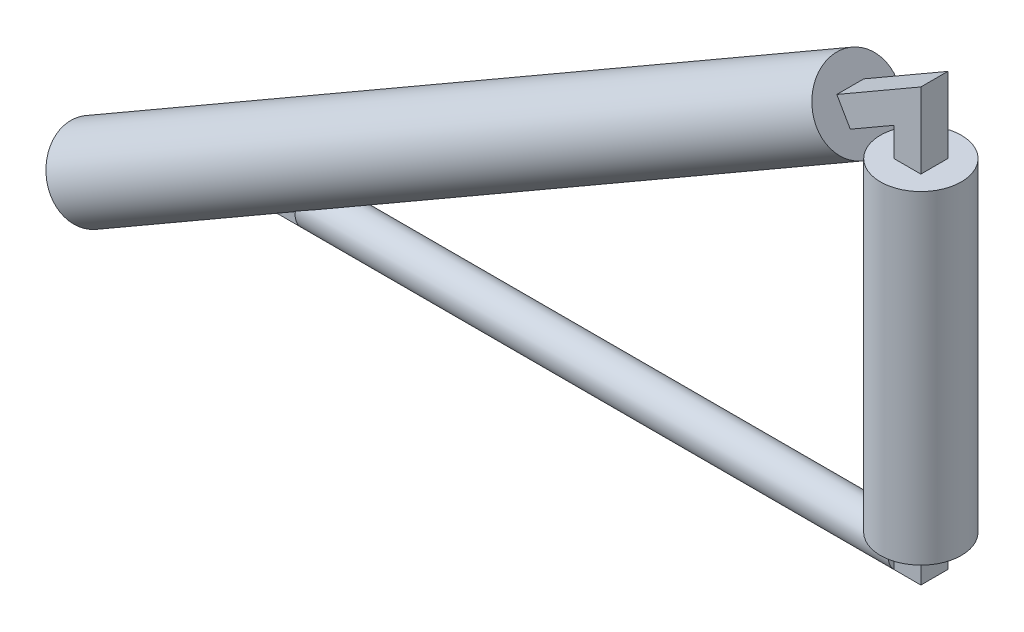
SolidWorks part; units mm, degrees
ref_plane "Front Plane" through (0, 0, 0) normal (0, 0, 1) x (1, 0, 0)
ref_plane "Top Plane" through (0, 0, 0) normal (0, 1, 0) x (1, 0, 0)
ref_plane "Right Plane" through (0, 0, 0) normal (1, 0, 0) x (0, 0, -1)
sketch "Sketch1" plane through (0, 0, 0) normal (0, 0, 1) x (1, 0, 0)
  line L0 (0, 0) -> (0, 50.8)
  line L1 (0, 50.8) -> (-87.9882, 0)
  line L2 (-87.9882, 0) -> (0, 0)
  line L3 (-76.1389, 3.175) -> (-3.175, 3.175)
  line L4 (-3.175, 3.175) -> (-3.175, 45.3007)
  line L5 (-3.175, 45.3007) -> (-76.1389, 3.175)
  dimension "D1" = 101.6
  dimension "D2" = 30
  dimension "D3" = 3.175
extrude "Boss-Extrude1" add sketch "Sketch1" along normal blind 3.175
sketch "Sketch2" plane through (0, 0, 0) normal (1, 0, 0) x (0, 0, -1)
  line L0 (0, 0) -> (0, 50.8) construction
  line L1 (-3.175, 0) -> (0, 0) construction
  circle A0 centre (-1.5875, 1.5875) radius 2.2451
  dimension "D2" = 1.5875
  dimension "D1" = 1.5875
extrude "Boss-Extrude2" add sketch "Sketch2" against normal blind 69.85 from surface at -3.175 starting at face at (-3.175, 24.2379, 1.5875)
ref_plane "Plane1" through (0, 22.86, 0) normal (0, -1, 0) x (-1, 0, 0)
sketch "Sketch4" plane through (0, 22.86, 0) normal (0, -1, 0) x (-1, 0, 0)
  line L0 (3.175, 0) -> (0, 0) construction
  line L1 (0, -3.175) -> (0, 0) construction
  circle A0 centre (1.5875, -1.5875) radius 4.7625
  dimension "D3" = 9.525
  dimension "D1" = 1.5875
  dimension "D2" = 1.5875
extrude "Boss-Extrude4" add sketch "Sketch4" along normal mid plane 38.1
ref_plane "Plane2" through (-21.997, 38.1, 0) normal (-0.5, 0.866, 0) x (0.866, 0.5, 0)
ref_plane "Plane3" through (0, 0, 0) normal (-0.866, -0.5, 0) x (0, 0, -1)
ref_plane "Plane4" through (-32.9956, -19.05, 0) normal (-0.866, -0.5, 0) x (0, 0, -1)
sketch "Sketch5" plane through (-32.9956, -19.05, 0) normal (-0.866, -0.5, 0) x (0, 0, -1)
  line L0 (0, -43.9941) -> (0, -36.5125) construction
  line L1 (-1.7463, -43.9941) -> (1.7463, -43.9941) construction
  circle A0 centre (-1.5875, -42.4066) radius 4.7625
  dimension "D3" = 9.525
  dimension "D1" = 1.5875
  dimension "D2" = 1.5875
extrude "Boss-Extrude5" add sketch "Sketch5" along normal mid plane 104.14
